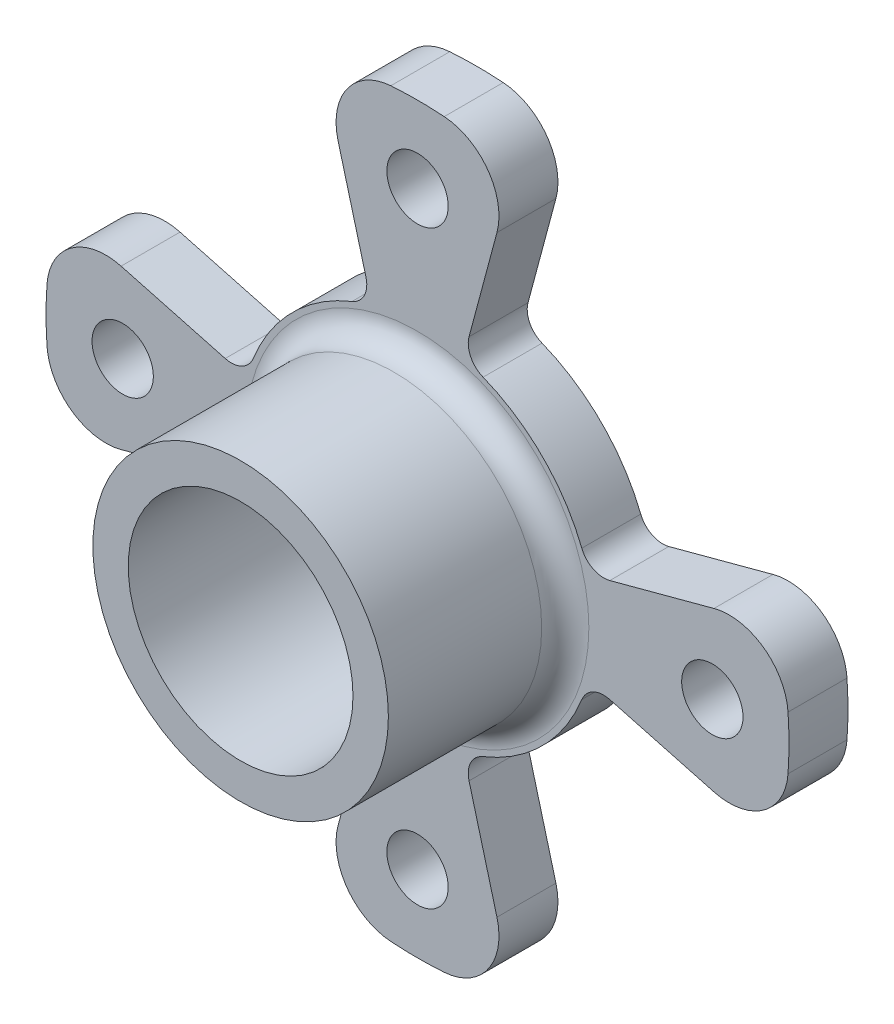
SolidWorks part; units mm, degrees
ref_plane "Front Plane" through (0, 0, 0) normal (0, 0, 1) x (1, 0, 0)
ref_plane "Top Plane" through (0, 0, 0) normal (0, 1, 0) x (1, 0, 0)
ref_plane "Right Plane" through (0, 0, 0) normal (1, 0, 0) x (0, 0, -1)
sketch "Sketch1" plane through (0, 0, 0) normal (0, 0, 1) x (1, 0, 0)
  circle A0 centre (0, 0) radius 31.5
  circle A1 centre (0, 0) radius 25
  circle A2 centre (0, 25) radius 2.6
  circle A3 centre (25, 0) radius 2.6
  circle A4 centre (0, -25) radius 2.6
  circle A5 centre (-25, 0) radius 2.6
  point P15 (0, 0)
  dimension "D1" = 63
  dimension "D2" = 50
  dimension "D3" = 5.2
  dimension "D4" = 4
extrude "Boss-Extrude1" add sketch "Sketch1" along normal blind 5 contours A0 A5 A1 A2 A3 A4 | A5 A1 A4 A3 A2
sketch "Sketch2" plane through (0, 0, 5) normal (0, 0, 1) x (1, 0, 0)
  circle A0 centre (0, 0) radius 12.53
  circle A1 centre (0, 0) radius 9.53
  dimension "D1" = 19.06
  dimension "D2" = 3
extrude "Boss-Extrude2" add sketch "Sketch2" along normal blind 15
sketch "Sketch3" plane through (0, 0, 5) normal (0, 0, 1) x (1, 0, 0)
  line L0 (0, 15) -> (0, 31.5) construction
  line L1 (0, 0) -> (8.1528, 30.4267)
  line L2 (0, 0) -> (-8.1528, 30.4267)
  line L3 (0, 0) -> (30.4267, 8.1528)
  line L4 (0, 0) -> (30.4267, -8.1528)
  line L5 (0, 0) -> (8.1528, -30.4267)
  line L6 (0, 0) -> (-8.1528, -30.4267)
  line L7 (0, 0) -> (-30.4267, -8.1528)
  line L8 (0, 0) -> (-30.4267, 8.1528)
  circle A0 centre (0, 0) radius 31.5
  circle A1 centre (0, 0) radius 15
  point P17 (0, 0)
  circle M11 centre (0, 0) radius 31.5
  dimension "D4" = 30
  dimension "D1" = 15
  dimension "D2" = 15
  dimension "D3" = 4
extrude "Cut-Extrude1" cut sketch "Sketch3" against normal blind 7 contours A1 L2 L8 M11 | A1 L3 L1 M11 | A1 L5 L4 M11 | A1 L7 L6 M11
fillet "Fillet1" radius 5 8 edges at (-30.4267, -8.1528, 2.5) (-8.1528, -30.4267, 2.5) (8.1528, -30.4267, 2.5) (30.4267, -8.1528, 2.5) (30.4267, 8.1528, 2.5) (-30.4267, 8.1528, 2.5) (-8.1528, 30.4267, 2.5) (8.1528, 30.4267, 2.5)
fillet "Fillet2" radius 2 8 edges at (14.4889, 3.8823, 2.5) (3.8823, 14.4889, 2.5) (-14.4889, 3.8823, 2.5) (-3.8823, 14.4889, 2.5) (-3.8823, -14.4889, 2.5) (-14.4889, -3.8823, 2.5) (3.8823, -14.4889, 2.5) (14.4889, -3.8823, 2.5)
fillet "Fillet3" radius 2 1 edges at (12.53, 0, 5)
